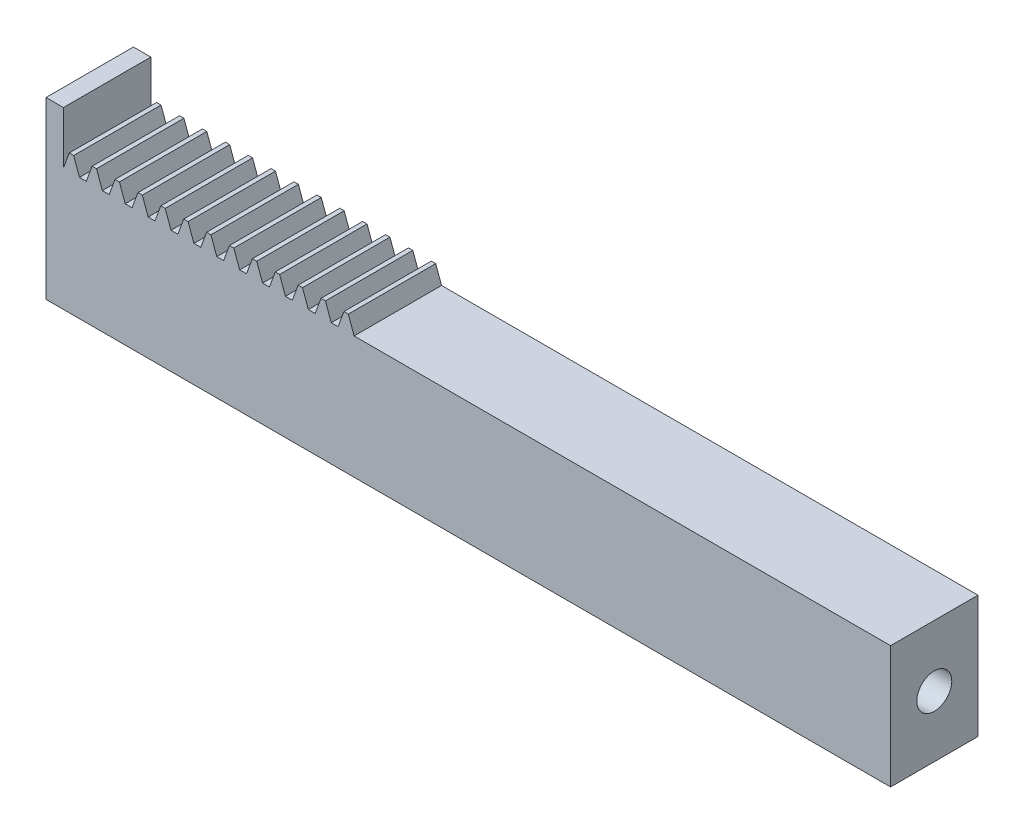
SolidWorks part; units mm, degrees
ref_plane "Plane1" through (0, 0, 0) normal (0, 0, 1) x (1, 0, 0)
ref_plane "Plane2" through (0, 0, 0) normal (0, 1, 0) x (1, 0, 0)
ref_plane "Plane3" through (0, 0, 0) normal (1, 0, 0) x (0, 0, -1)
sketch "HoldingSke" plane through (0, 0, 0) normal (0, 1, 0) x (1, 0, 0)
  line L0 (0, 0) -> (466.9807, -391.8433)
  line L1 (-15, 0) -> (100, 0) construction
  line L2 (0, 0) -> (-2.1039, 2.3779)
  line L3 (0, 0) -> (-11.863, 4.5341)
  line L4 (0, 0) -> (7.8894, 3.5126)
  line L5 (0, 0) -> (-23.7986, -8.8762)
  line L6 (0, 0) -> (-10.5278, -7.1032)
  line L9 (-71.009, 38.7566) -> (0.5956, 64.8185)
  line L10 (-76.2, 71.12) -> (-57.15, 71.12)
  line L11 (0, 0) -> (-12.7, 0)
  line L12 (-76.2, 101.6) -> (-76.1573, 101.6)
  line L13 (24.9733, 27.94) -> (52.9518, 28.4284)
  line L14 (24.9733, 27.94) -> (25.0241, 27.9398)
  line L15 (24.9733, 27.94) -> (100.4021, 29.52)
  circle A0 centre (0, 0) radius 19.05
  circle A1 centre (0, 0) radius 9.525
  circle A2 centre (0, 0) radius 12.7
  dimension "MPH" = 19.05
  dimension "Diameter" = 38.1
  dimension "Num_teeth" = 24
  dimension "Pitch" = 609.6
  dimension "Width" = 12.7
  dimension "Show_teeth" = 400
  dimension "Thickness" = 12.7
  dimension "Ap" = 20
  dimension "Pitch_height" = 19.05
  dimension "Backlash" = 0.0427
  dimension "Addendum_fac" = 1
  dimension "Dedendum_fac" = 1.2
  dimension "Clearance_fac" = 0.2
  dimension "Dedendum_add" = 0.0508
  dimension "Length" = 76.2
sketch "BlankSke" plane through (0, 0, 0) normal (0, 0, 1) x (1, 0, 0)
  line L1 (0, 0) -> (76.2, 0)
  line L2 (0, 0) -> (0, 20.1083)
  line L3 (0, 20.1083) -> (76.2, 20.1083)
  line L4 (76.2, 0) -> (76.2, 20.1083)
  dimension "Length" = 76.2
  dimension "Blank_height" = 20.1083
extrude "Blank" add sketch "BlankSke" against normal blind 12.7
sketch "TooCutSkeIll" plane through (0, 0, 0) normal (0, 0, 1) x (1, 0, 0)
  line L0 (-1.3343, 20.0805) -> (-0.5598, 17.9527)
  line L1 (-0.3132, 17.78) -> (0.3132, 17.78)
  line L2 (0.5598, 17.9527) -> (1.3343, 20.0805)
  line L3 (76.2, 20.1083) -> (0, 20.1083) construction
  line L4 (0, 0) -> (0, 64.897) construction
  line L5 (-13.208, 19.05) -> (12.954, 19.05) construction
  line L6 (0, 0) -> (76.2, 0) construction
  line L7 (0.9592, 19.05) -> (0.9592, 48.7463) construction
  line L8 (-0.9592, 19.05) -> (-0.9592, 48.7463) construction
  line L9 (1.3741, 20.1083) -> (1.3741, 20.1337)
  line L10 (-1.3741, 20.1083) -> (-1.3741, 20.1337)
  line L11 (-1.3741, 20.1337) -> (1.3741, 20.1337)
  arc A0 (0.3132, 17.78) -> (0.5598, 17.9527) centre (0.3132, 18.0425) ccw
  arc A1 (-0.5598, 17.9527) -> (-0.3132, 17.78) centre (-0.3132, 18.0425) ccw
  arc A2 (1.3741, 20.1083) -> (1.3343, 20.0805) centre (1.3741, 20.066) ccw
  arc A3 (-1.3343, 20.0805) -> (-1.3741, 20.1083) centre (-1.3741, 20.066) ccw
  dimension "Root_fillet" = 0.2625
  dimension "Break_rad" = 0.0423
  dimension "Pitch_height" = 19.05
  dimension "Gap_width" = 1.9185
  dimension "Dedendum" = 1.27
  dimension "Addendum_plus" = 1.0837
  dimension "Pressure_angle" = 20
extrude "ToothCutIll" [suppressed] cut sketch "TooCutSkeIll" against normal through all
sketch "TooCutSkeSim" plane through (0, 0, 0) normal (0, 0, 1) x (1, 0, 0)
  line L0 (0.497, 17.78) -> (-0.497, 17.78)
  line L1 (1.3537, 20.1337) -> (0.497, 17.78)
  line L2 (0, 17.4625) -> (0, 53.467) construction
  line L3 (1.3537, 20.1337) -> (-1.3537, 20.1337)
  line L6 (-1.3537, 20.1337) -> (-0.497, 17.78)
  line L9 (-0.9592, 19.05) -> (0.9592, 19.05) construction
  line L10 (0, 0) -> (76.2, 0) construction
  line L11 (0.9592, 19.05) -> (0.9592, 53.467) construction
  line L12 (-0.9592, 19.05) -> (-0.9592, 53.467) construction
  dimension "Pitch_height" = 19.05
  dimension "Pressure_angle" = 20
  dimension "Gap_width" = 1.9185
  dimension "Dedendum" = 1.27
  dimension "Addendum_plus" = 1.0837
extrude "ToothCutSim" cut sketch "TooCutSkeSim" against normal through all
pattern_linear "TeethCuts" count 24 spacing 3.3249 along (1, 0, 0) of "ToothCutSim"
sketch "Sketch1" plane through (76.2, 0, 0) normal (1, 0, 0) x (0, 0, -1)
  line L4 (12.7, 17.78) -> (0, 17.78)
  line L5 (0, 17.78) -> (0, 0)
  line L6 (0, 0) -> (12.7, 0)
  line L7 (12.7, 0) -> (12.7, 17.78)
  line L8 (12.7, 17.78) -> (0, 17.78)
  line L9 (0, 17.78) -> (0, 0)
  line L10 (0, 0) -> (12.7, 0)
  line L11 (12.7, 0) -> (12.7, 17.78)
  dimension "D1" = 0
extrude "Boss-Extrude1" add sketch "Sketch1" along normal blind 44.45
sketch "Sketch2" plane through (0, 0, 0) normal (0, 0, 1) x (1, 0, 0)
  line L0 (2.4041, 18.9442) -> (75.57, 18.8918) construction
  line L1 (2.8279, 17.78) -> (1.9804, 20.1083) construction
  line L2 (75.9746, 17.78) -> (75.1272, 20.1083) construction
sketch "Sketch3" plane through (120.65, 0, -120.65) normal (-1, 0, 0) x (0, 0, 1)
  line L0 (120.65, 8.89) -> (114.3, 8.89) construction
  line L1 (120.65, 17.78) -> (120.65, 0) construction
  line L2 (114.3, 17.78) -> (114.3, 0) construction
  line L7 (120.65, 0) -> (107.95, 0) construction
  circle A0 centre (114.3, 8.89) radius 2.54
  dimension "D1" = 6.35
  dimension "D2" = 5.08
extrude "Cut-Extrude1" cut sketch "Sketch3" along normal blind 12.7
sketch "Sketch4" plane through (0, 17.78, 0) normal (0, 1, 0) x (1, 0, 0)
  line L4 (0, 12.7) -> (0, 0)
  line L5 (0, 0) -> (0.497, 0)
  line L6 (0.497, 0) -> (0.497, 12.7)
  line L7 (0.497, 12.7) -> (0, 12.7)
  line L8 (0, 12.7) -> (0, 0)
  line L9 (0, 0) -> (0.497, 0)
  line L10 (0.497, 0) -> (0.497, 12.7)
  line L11 (0.497, 12.7) -> (0, 12.7)
  dimension "D1" = 0
extrude "Boss-Extrude2" add sketch "Sketch4" along normal blind 7.62
sketch "Sketch5" plane through (0, 0, 0) normal (-1, 0, 0) x (0, 0, 1)
  line L4 (0, 0) -> (0, 25.4)
  line L5 (0, 25.4) -> (-12.7, 25.4)
  line L6 (-12.7, 25.4) -> (-12.7, 0)
  line L7 (-12.7, 0) -> (0, 0)
  line L8 (0, 0) -> (0, 25.4)
  line L9 (0, 25.4) -> (-12.7, 25.4)
  line L10 (-12.7, 25.4) -> (-12.7, 0)
  line L11 (-12.7, 0) -> (0, 0)
  dimension "D1" = 0
extrude "Boss-Extrude3" add sketch "Sketch5" along normal blind 2.032
sketch "Sketch6" plane through (120.65, 0, 0) normal (1, 0, 0) x (0, 0, -1)
  line L1 (0, 17.78) -> (12.7, 17.78)
  line L2 (0, 17.78) -> (0, 20.1083)
  line L3 (0, 20.1083) -> (12.7, 20.1083)
  line L4 (12.7, 17.78) -> (12.7, 20.1083)
extrude "Cut-Extrude2" cut sketch "Sketch6" against normal blind 76.962
equation "' \"Pitch@HoldingSke\" = 4"
equation "' \"Num_teeth@HoldingSke\" = 12"
equation "' \"Ap@HoldingSke\" =  20"
equation "' \"Width@HoldingSke\" = 0.25"
equation "' \"Show_teeth@HoldingSke\" = 500"
equation "' \"Backlash@HoldingSke\" = 0.009"
equation "' \"Addendum_fac@HoldingSke\" = 1.0"
equation "' \"Dedendum_fac@HoldingSke\" = 1.25"
equation "' \"Dedendum_add@HoldingSke\" = 0.00005"
equation "' \"Clearance_fac@HoldingSke\" = 0.25"
equation "' \"Pitch_height@HoldingSke\" = 1"
equation "' \"Length@HoldingSke\" = 4.71"
equation "\"MPH@HoldingSke\" = \"Dedendum_fac@HoldingSke\" / \"Pitch@HoldingSke\" + 2 * \"Dedendum_add@HoldingSke\" + 0.002"
equation "\"MPH@HoldingSke\" = ((sgn( \"MPH@HoldingSke\" - \"Pitch_height@HoldingSke\")+1)*( \"MPH@HoldingSke\" - \"Pitch_height@HoldingSke\"))/2 + \"Pitch_height@HoldingSke\""
equation "\"Blank_height@BlankSke\" = \"Pitch_height@HoldingSke\" + \"Addendum_fac@HoldingSke\"  / \"Pitch@HoldingSke\" "
equation "\"Length@BlankSke\" =  \"Length@HoldingSke\""
equation "\"Face_width@Blank\" = \"Width@HoldingSke\""
equation "\"Pressure_angle@TooCutSkeIll\" = \"Ap@HoldingSke\""
equation "\"Addendum_plus@TooCutSkeIll\" =  \"Addendum_fac@HoldingSke\"  / \"Pitch@HoldingSke\" + 0.001"
equation "\"Dedendum@TooCutSkeIll\" = \"Dedendum_fac@HoldingSke\"  / \"Pitch@HoldingSke\""
equation "\"Pitch_height@TooCutSkeIll\" =  \"MPH@HoldingSke\""
equation "\"Gap_width@TooCutSkeIll\" = 3.14159265 / 2 / \"Pitch@HoldingSke\" + 6 * \"Backlash@HoldingSke\""
equation "\"Pressure_angle@TooCutSkeSim\" = \"Ap@HoldingSke\""
equation "\"Addendum_plus@TooCutSkeSim\" =  \"Addendum_fac@HoldingSke\"  / \"Pitch@HoldingSke\" + 0.001"
equation "\"Dedendum@TooCutSkeSim\" = \"Dedendum_fac@HoldingSke\"  / \"Pitch@HoldingSke\""
equation "\"Pitch_height@TooCutSkeSim\" =  \"MPH@HoldingSke\""
equation "\"Gap_width@TooCutSkeSim\" = 3.14159265 / 2 / \"Pitch@HoldingSke\" + 6 * \"Backlash@HoldingSke\""
equation "\"Root_fillet@TooCutSkeIll\" = \"Clearance_fac@HoldingSke\" / \"Pitch@HoldingSke\" + \"Dedendum_add@HoldingSke\""
equation "\"Break_rad@TooCutSkeIll\" = 0.02 / \"Pitch@HoldingSke\" * 2"
equation "\"Linear_pitch@TeethCuts\" = 3.14159265 / \"Pitch@HoldingSke\""
equation "\"Num_teeth@HoldingSke\" = int( ( \"Length@HoldingSke\" + 0 ) / (3.14159265 / \"Pitch@HoldingSke\")) + 0.9999  + 1"
equation " \"Num_teeth@TeethCuts\" = int( \"Show_teeth@HoldingSke\" ) + 1"
equation " \"Num_teeth@TeethCuts\" = ((sgn( \"Num_teeth@TeethCuts\" - \"Num_teeth@HoldingSke\" )-1)*( \"Num_teeth@TeethCuts\" - \"Num_teeth@HoldingSke\" ))/-2+ \"Num_teeth@HoldingSke\""
equation " \"Num_teeth@TeethCuts\" = ((sgn( \"Num_teeth@TeethCuts\" - 2.0)+1)*( \"Num_teeth@TeethCuts\" - 2.0))/2 +2.0"
